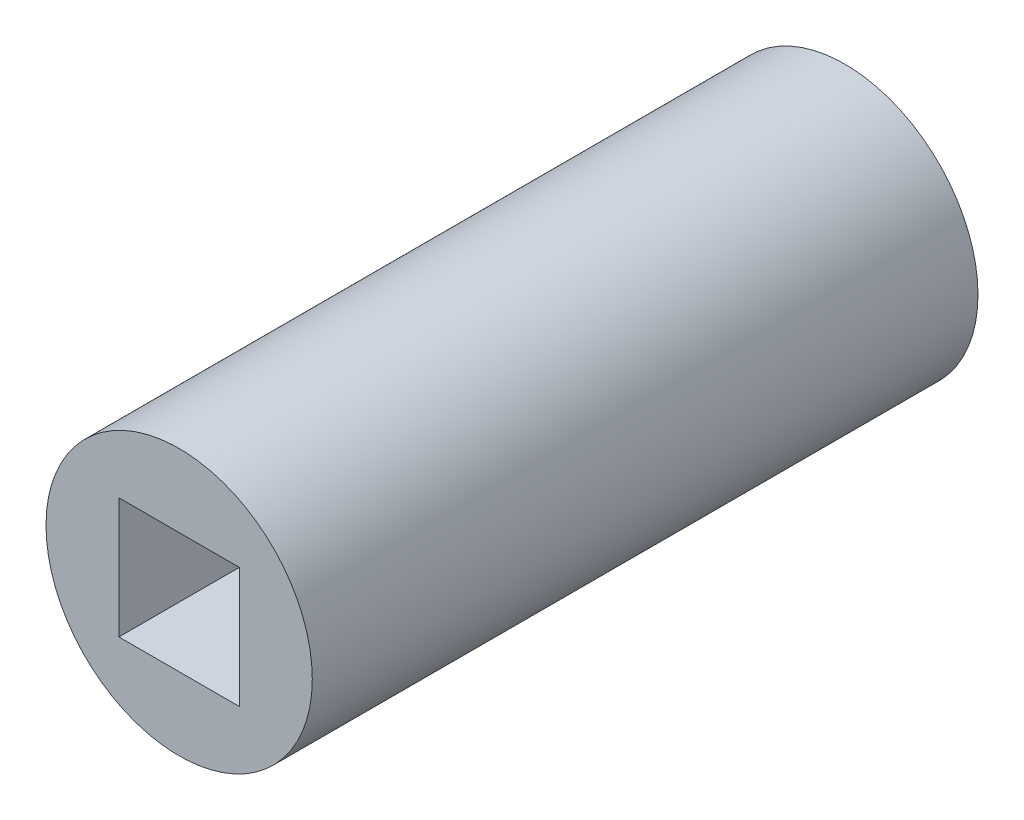
SolidWorks part; units mm, degrees
ref_plane "Front Plane" through (0, 0, 0) normal (0, 0, 1) x (1, 0, 0)
ref_plane "Top Plane" through (0, 0, 0) normal (0, 1, 0) x (1, 0, 0)
ref_plane "Right Plane" through (0, 0, 0) normal (1, 0, 0) x (0, 0, -1)
sketch "Sketch1" plane through (0, 0, 0) normal (0, 0, 1) x (1, 0, 0)
  line L0 (-2, 1.5) -> (2, 1.5)
  line L2 (-2.4495, 2.5) -> (2.4495, 2.5) construction
  arc A0 (-2, 1.5) -> (2, 1.5) centre (0, 0) ccw
  arc A1 (-2.4495, 2.5) -> (2.4495, 2.5) centre (0, 0) ccw
  arc A2 (-2.4495, 2.5) -> (2.4495, 2.5) centre (0, 0) cw
  dimension "D1" = 5
  dimension "D4" = 3.5
  dimension "D2" = 4
  dimension "D3" = 1
extrude "Boss-Extrude1" add sketch "Sketch1" along normal blind 10
sketch "Sketch2" plane through (0, 0, 10) normal (0, 0, 1) x (1, 0, 0)
  circle A0 centre (0, 0) radius 3.5
  dimension "D1" = 7
extrude "Boss-Extrude2" add sketch "Sketch2" along normal blind 7.5 contours A0
sketch "Sketch3" plane through (0, 0, 17.5) normal (0, 0, 1) x (1, 0, 0)
  line L1 (-1.5838, -1.5838) -> (1.5838, -1.5838)
  line L2 (-1.5838, -1.5838) -> (-1.5838, 1.5838)
  line L3 (-1.5838, 1.5838) -> (1.5838, 1.5838)
  line L4 (1.5838, -1.5838) -> (1.5838, 1.5838)
  line L5 (-1.5838, -1.5838) -> (1.5838, 1.5838) construction
  line L6 (-1.5838, 1.5838) -> (1.5838, -1.5838) construction
  point P0 (0, 0)
  dimension "D1" = 3.1676
  dimension "D2" = 3.1676
extrude "Cut-Extrude1" cut sketch "Sketch3" against normal blind 5
